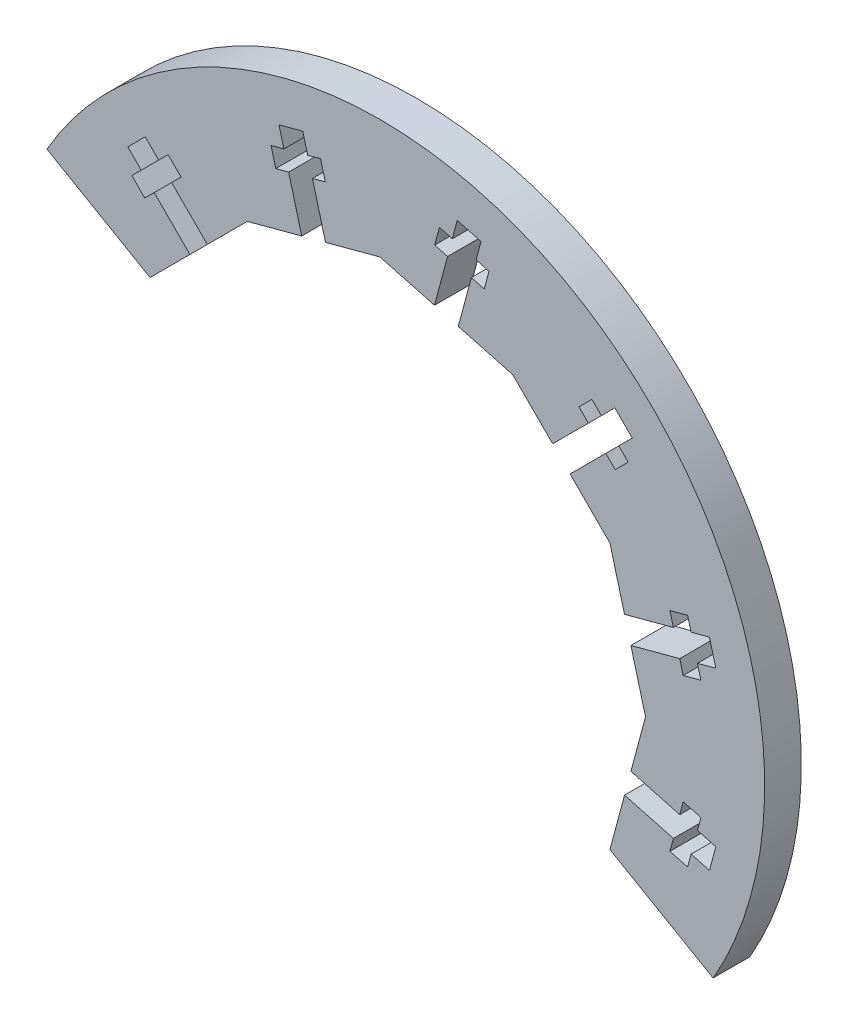
SolidWorks part; units mm, degrees
ref_plane "Front Plane" through (0, 0, 0) normal (0, 0, 1) x (1, 0, 0)
ref_plane "Top Plane" through (0, 0, 0) normal (0, 1, 0) x (1, 0, 0)
ref_plane "Right Plane" through (0, 0, 0) normal (1, 0, 0) x (0, 0, -1)
sketch "Sketch1" plane through (0, 0, 0) normal (0, 0, 1) x (1, 0, 0)
  line L0 (-39.444, 0) -> (39.444, 0) construction
  line L1 (0, -39.444) -> (0, 39.444) construction
  line L2 (-21.3655, 40.2932) -> (-1.6435, 45.5777) construction
  line L3 (0, 46.018) -> (-23.009, 39.8528)
  line L4 (-23.009, 39.8528) -> (-39.8528, 23.009)
  line L5 (-39.8528, 23.009) -> (-46.018, 0)
  line L6 (-46.018, 0) -> (-39.8528, -23.009)
  line L7 (-39.8528, -23.009) -> (-23.009, -39.8528)
  line L8 (-23.009, -39.8528) -> (0, -46.018)
  line L9 (0, -46.018) -> (23.009, -39.8528)
  line L10 (23.009, -39.8528) -> (39.8528, -23.009)
  line L11 (39.8528, -23.009) -> (46.018, 0)
  line L12 (46.018, 0) -> (39.8528, 23.009)
  line L13 (39.8528, 23.009) -> (23.009, 39.8528)
  line L14 (23.009, 39.8528) -> (0, 46.018)
  circle A0 centre (0, 0) radius 66.675
  circle A1 centre (0, 0) radius 44.45 construction
  dimension "D1" = 22.225
extrude "Boss-Extrude1" add sketch "Sketch1" against normal blind 6.35
sketch "Sketch2" plane through (0, 0, 0) normal (0, 0, 1) x (1, 0, 0)
  line L0 (0, -39.444) -> (0, 39.444) construction
  line L1 (-39.444, 0) -> (39.444, 0) construction
  line L2 (43.4446, -11.641) -> (10.9663, -2.9384) construction
  line L6 (34.1595, -19.722) -> (40.2932, -21.3655) construction
  line L7 (39.444, 0) -> (45.5777, -1.6435) construction
  line L8 (45.5777, -1.6435) -> (40.2932, -21.3655) construction
  line B0 (43.4876, -9.4436) -> (42.3832, -13.5654)
  line B1 (53.9144, -16.6552) -> (53.3162, -18.8878)
  line B2 (53.3162, -18.8878) -> (50.2494, -18.0661)
  line B3 (50.2494, -18.0661) -> (50.8476, -15.8334)
  line B4 (50.8476, -15.8334) -> (42.3832, -13.5654)
  line B5 (53.9144, -16.6552) -> (57.1039, -17.5098)
  line B6 (57.1039, -17.5098) -> (58.2083, -13.388)
  line B7 (55.0188, -12.5334) -> (58.2083, -13.388)
  line B8 (51.952, -11.7116) -> (43.4876, -9.4436)
  line B9 (52.5503, -9.479) -> (51.952, -11.7116)
  line B10 (55.6171, -10.3007) -> (52.5503, -9.479)
  line B11 (55.0188, -12.5334) -> (55.6171, -10.3007)
sketch_block_instance "TSlot-1"
sketch_block "TSlot" parameters "D1"=3.302, "D2"=3.175
extrude "Cut-Extrude1" cut sketch "Sketch2" against normal through all
pattern_circular "CirPattern1" count 6 every 30 about axis through (0, 0, 0) along (0, 0, 1) of "Cut-Extrude1"
sketch "Sketch3" plane through (0, 0, -6.35) normal (0, 0, -1) x (-1, 0, 0)
  line L0 (-57.7422, -33.3375) -> (57.7422, 33.3375)
  circle A0 centre (0, 0) radius 66.675
  circle A1 centre (0, 0) radius 66.675 construction
extrude "Cut-Extrude2" cut sketch "Sketch3" against normal blind 6.35 contours L0 A0
